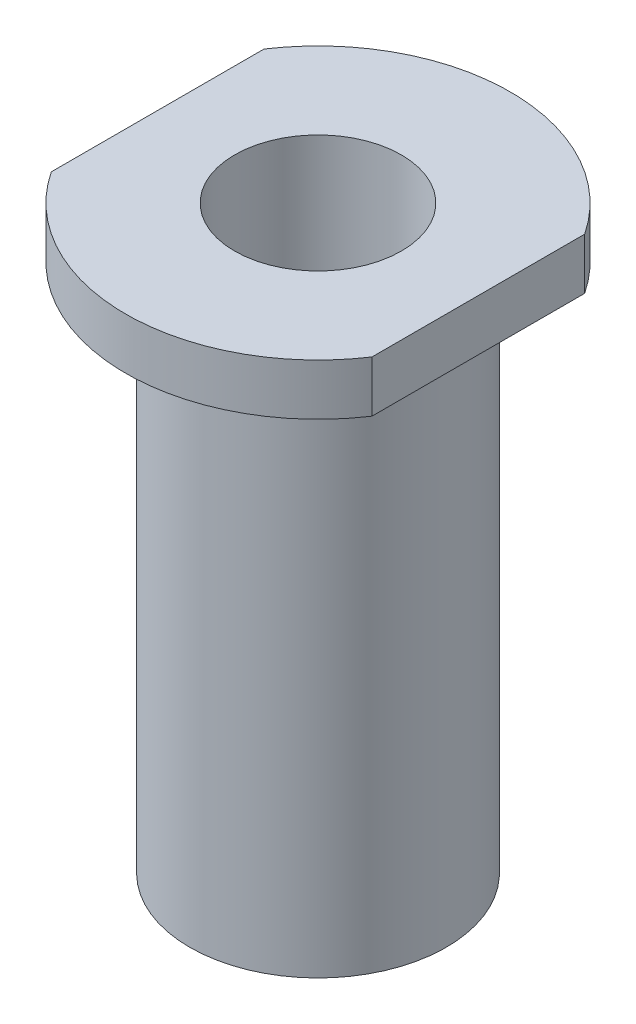
SolidWorks part; units mm, degrees
ref_plane "Front Plane" through (0, 0, 0) normal (0, 0, 1) x (1, 0, 0)
ref_plane "Top Plane" through (0, 0, 0) normal (0, 1, 0) x (1, 0, 0)
ref_plane "Right Plane" through (0, 0, 0) normal (1, 0, 0) x (0, 0, -1)
sketch "Sketch1" plane through (0, 0, 0) normal (0, 1, 0) x (1, 0, 0)
  circle A0 centre (0, 0) radius 5
  dimension "D1" = 10
extrude "Boss-Extrude1" add sketch "Sketch1" along normal blind 22.63
sketch "Sketch2" plane through (0, 22.63, 0) normal (0, 1, 0) x (1, 0, 0)
  circle A0 centre (0, 0) radius 3.25
  dimension "D1" = 6.5
extrude "Cut-Extrude1" cut sketch "Sketch2" against normal blind 9.652
sketch "Sketch3" plane through (0, 12.978, 0) normal (0, 1, 0) x (1, 0, 0)
  circle A0 centre (0, 0) radius 2.5
  dimension "D1" = 5
extrude "Cut-Extrude2" cut sketch "Sketch3" against normal offset from surface (9.978 mm away) 3 up to face at (0, 0, 5)
sketch "Sketch4" plane through (0, 3, 0) normal (0, 1, 0) x (1, 0, 0)
  circle A0 centre (0, 0) radius 1.5
  dimension "D1" = 3
extrude "Cut-Extrude3" cut sketch "Sketch4" against normal blind 3
sketch "Sketch5" plane through (0, 22.63, 0) normal (0, 1, 0) x (1, 0, 0)
  line L1 (6.25, -4.1458) -> (-6.25, -4.1458) construction
  line L2 (6.25, -4.1458) -> (6.25, 4.1458)
  line L3 (6.25, 4.1458) -> (-6.25, 4.1458) construction
  line L4 (-6.25, -4.1458) -> (-6.25, 4.1458)
  line L5 (6.25, -4.1458) -> (-6.25, 4.1458) construction
  line L6 (6.25, 4.1458) -> (-6.25, -4.1458) construction
  circle A0 centre (0, 0) radius 5
  arc A1 (-6.25, -4.1458) -> (6.25, -4.1458) centre (0, 0) ccw
  arc A2 (-6.25, 4.1458) -> (-6.25, -4.1458) centre (0, 0) ccw construction
  arc A3 (6.25, 4.1458) -> (-6.25, 4.1458) centre (0, 0) ccw
  arc A4 (6.25, -4.1458) -> (6.25, 4.1458) centre (0, 0) ccw construction
  dimension "D1" = 15
  dimension "D2" = 12.5
extrude "Boss-Extrude3" add sketch "Sketch5" against normal blind 2
